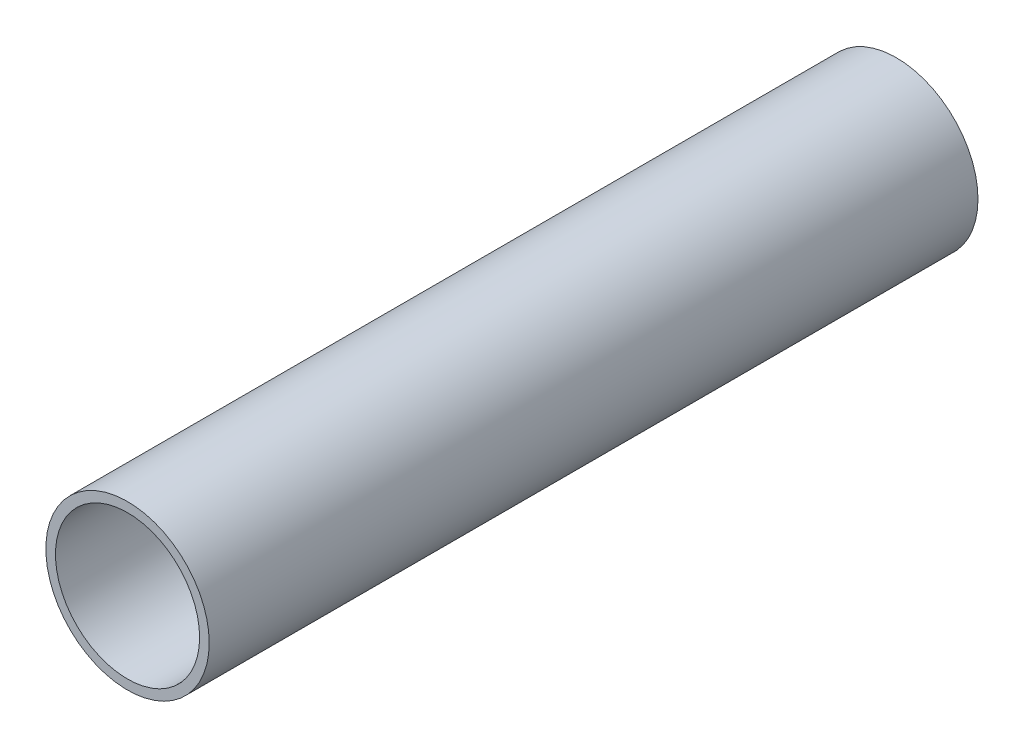
SolidWorks part; units mm, degrees
ref_plane "Front Plane" through (0, 0, 0) normal (0, 0, 1) x (1, 0, 0)
ref_plane "Top Plane" through (0, 0, 0) normal (0, 1, 0) x (1, 0, 0)
ref_plane "Right Plane" through (0, 0, 0) normal (1, 0, 0) x (0, 0, -1)
sketch "Sketch1" plane through (0, 0, 0) normal (0, 0, 1) x (1, 0, 0)
  circle A0 centre (0, 0) radius 37.5
  circle A1 centre (0, 0) radius 42.5
  dimension "D1" = 5
extrude "Boss-Extrude1" add sketch "Sketch1" along normal blind 400
